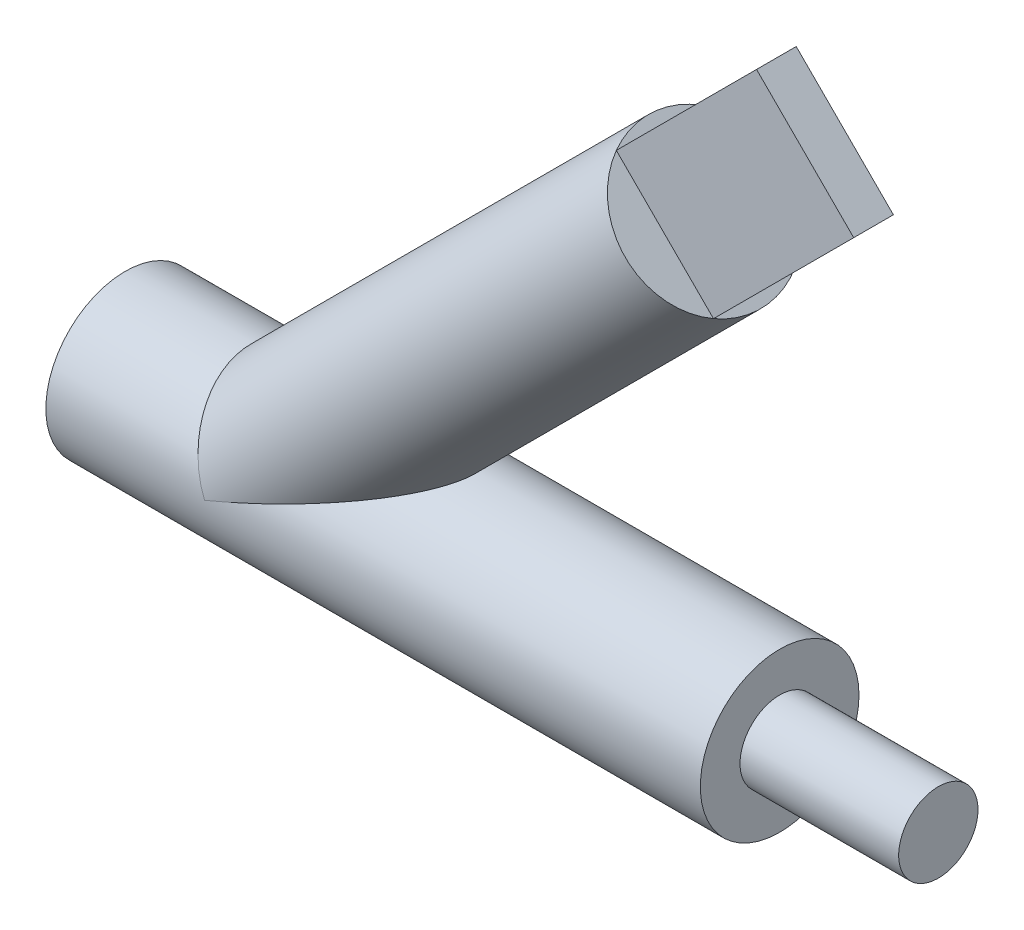
SolidWorks part; units mm, degrees
ref_plane "Front Plane" through (0, 0, 0) normal (0, 0, 1) x (1, 0, 0)
ref_plane "Top Plane" through (0, 0, 0) normal (0, 1, 0) x (1, 0, 0)
ref_plane "Right Plane" through (0, 0, 0) normal (1, 0, 0) x (0, 0, -1)
sketch "Sketch1" plane through (0, 0, 0) normal (1, 0, 0) x (0, 0, -1)
  circle A0 centre (0, 0) radius 20
extrude "Boss-Extrude1" add sketch "Sketch1" along normal blind 165
sketch "Sketch2" plane through (165, 0, 0) normal (1, 0, 0) x (0, 0, -1)
  circle A0 centre (0, 0) radius 10
  dimension "D1" = 20
extrude "Boss-Extrude2" add sketch "Sketch2" along normal blind 40
sketch "Sketch4" plane through (0, 0, 0) normal (0, 1, 0) x (1, 0, 0)
  line L0 (40, -34.1123) -> (40, 43.0803)
  line L1 (0, 20) -> (0, -20) construction
  circle A0 centre (40, 0) radius 15
  dimension "D1" = 40
ref_plane "Plane1" through (20, 20, 0) normal (0.7071, 0.7071, 0) x (0.7071, -0.7071, 0)
sketch "Sketch5" plane through (20, 20, 0) normal (0.7071, 0.7071, 0) x (0.7071, -0.7071, 0)
  circle A0 centre (28.2843, 0) radius 20
extrude "Boss-Extrude3" add sketch "Sketch5" along normal blind 150 contours A0
sketch "Sketch6" plane through (126.066, 126.066, 0) normal (0.7071, 0.7071, 0) x (0, 0, -1)
  line L1 (0, -45.6048) -> (-10, -45.6048)
  line L2 (-10, -10.9638) -> (-10, -45.6048)
  line L4 (0, -45.6048) -> (0, -10.9638)
  line L7 (0, -10.9638) -> (-10, -10.9638)
  line L8 (-10, -45.6048) -> (-10, -10.9638)
  point P2 (0, -28.2843)
extrude "Boss-Extrude5" add sketch "Sketch6" along normal blind 50 contours L4 L7 L2 L1
sketch "Sketch7" plane through (0, 0, 0) normal (-1, 0, 0) x (0, 0, 1)
  circle A0 centre (0, 0) radius 5
extrude "Cut-Extrude1" cut sketch "Sketch7" against normal blind 10
